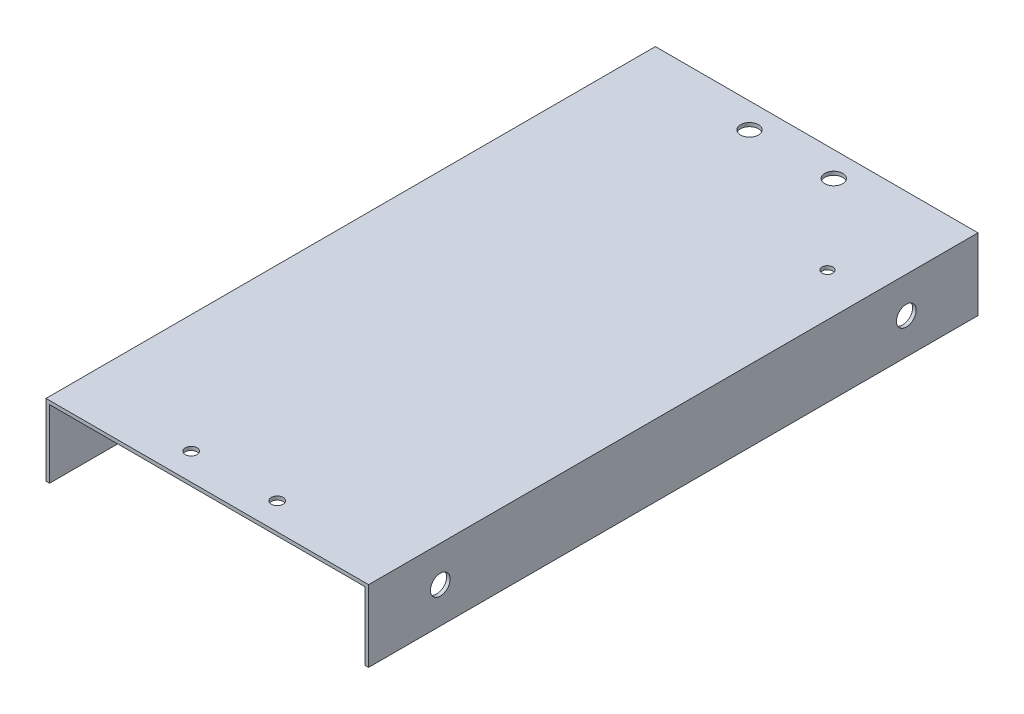
SolidWorks part; units mm, degrees
material "6061 Alloy"
ref_plane "Front Plane" through (0, 0, 0) normal (0, 0, 1) x (1, 0, 0)
ref_plane "Top Plane" through (0, 0, 0) normal (0, 1, 0) x (1, 0, 0)
ref_plane "Right Plane" through (0, 0, 0) normal (1, 0, 0) x (0, 0, -1)
sketch "Sketch1" plane through (0, 0, 0) normal (0, 0, 1) x (1, 0, 0)
  line L0 (-45, 1) -> (-45, 21)
  line L1 (-45, 21) -> (45, 21)
  line L2 (45, 21) -> (45, 1)
  line L3 (45, 1) -> (44, 1)
  line L4 (44, 1) -> (44, 20)
  line L5 (44, 20) -> (-44, 20)
  line L6 (-44, 20) -> (-44, 1)
  line L7 (-44, 1) -> (-45, 1)
  dimension "D1" = 90
  dimension "D2" = 1
  dimension "D3" = 1
  dimension "D4" = 1
  dimension "D5" = 45
  dimension "D6" = 20
  dimension "D7" = 20
  dimension "D8" = 20
extrude "Boss-Extrude1" add sketch "Sketch1" against normal blind 170
sketch "Sketch2" plane through (-45, 0, 0) normal (-1, 0, 0) x (0, 0, 1)
  line L0 (-170, 21) -> (-170, 1) construction
  line L1 (-170, 21) -> (0, 21) construction
  line L2 (0, 21) -> (0, 1) construction
  circle A0 centre (-150, 11) radius 2.75
  circle A1 centre (-20, 11) radius 2.75
  dimension "D1" = 5.5
  dimension "D4" = 5.5
  dimension "D2" = 20
  dimension "D3" = 10
  dimension "D5" = 20
  dimension "D6" = 10
extrude "Cut-Extrude1" cut sketch "Sketch2" against normal blind 90
sketch "Sketch3" plane through (0, 21, 0) normal (0, 1, 0) x (1, 0, 0)
  line L0 (0, 0) -> (0, 64.9693) construction
  line L1 (45, 0) -> (-45, 0) construction
  circle A0 centre (12, 7.5) radius 1.65
  circle A1 centre (-12, 7.5) radius 1.65
  dimension "D1" = 3.3
  dimension "D2" = 12
  dimension "D3" = 7.5
extrude "Cut-Extrude2" cut sketch "Sketch3" against normal blind 10
sketch "Sketch4" plane through (0, 21, 0) normal (0, 1, 0) x (1, 0, 0)
  line L0 (0, 170) -> (0, 120.7715) construction
  line L1 (45, 170) -> (-45, 170) construction
  circle A0 centre (-11.75, 163) radius 2.5
  circle A2 centre (11.75, 163) radius 2.5
  dimension "D1" = 5
  dimension "D2" = 11.75
  dimension "D3" = 7
extrude "Cut-Extrude3" cut sketch "Sketch4" against normal up to next
sketch "Sketch5" plane through (0, 21, 0) normal (0, 1, 0) x (1, 0, 0)
  line L0 (45, 170) -> (45, 0) construction
  line L1 (45, 170) -> (-45, 170) construction
  circle A0 centre (33, 140) radius 1.5
  dimension "D1" = 3
  dimension "D2" = 12
  dimension "D3" = 30
extrude "Cut-Extrude4" cut sketch "Sketch5" against normal up to next
